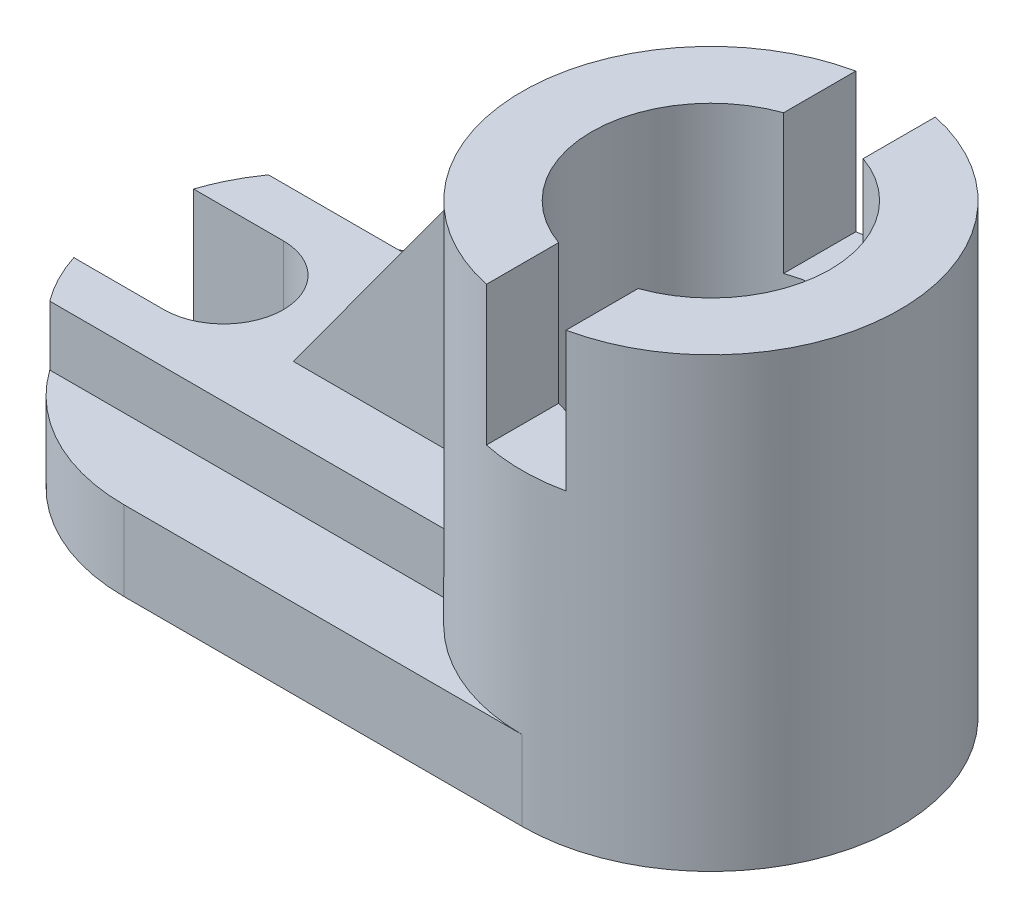
SolidWorks part; units mm, degrees
ref_plane "前视基准面" through (0, 0, 0) normal (0, 0, 1) x (1, 0, 0)
ref_plane "上视基准面" through (0, 0, 0) normal (0, 1, 0) x (1, 0, 0)
ref_plane "右视基准面" through (0, 0, 0) normal (1, 0, 0) x (0, 0, -1)
sketch "草图1" plane through (0, 0, 0) normal (0, 1, 0) x (1, 0, 0)
  circle A0 centre (0, 0) radius 19
  point P3 (-198.611, 7.7922)
sketch "草图2" plane through (0, 0, 0) normal (0, 1, 0) x (1, 0, 0)
  line L0 (-40, 19) -> (0, 19)
  line L1 (-40, -19) -> (0, -19)
  line L2 (0, 19) -> (0, -19)
  arc A0 (-40, 19) -> (-40, -19) centre (-40, 0) ccw
  circle A1 centre (0, 0) radius 19 construction
extrude "凸台-拉伸5" add sketch "草图1" along normal blind 45
extrude "凸台-拉伸7" add sketch "草图2" along normal blind 8
sketch "草图4" plane through (0, 8, 0) normal (0, 1, 0) x (1, 0, 0)
  line L0 (-10, 11) -> (-55.4919, 11)
  line L1 (-24.75, 0) -> (24.75, 0) construction
  line L2 (-10, -11) -> (-55.4919, -11)
  line L3 (-10, 11) -> (-10, -11)
  arc A1 (-40, 19) -> (-40, -19) centre (-40, 0) ccw construction
  spline S0 degree 3 poles (-55.4919, 11) (-60.0194, 4.7062) (-60.318, -4.5406) (-55.4919, -11) knots 0 0 0 0 1 1 1 1
  point P10 (0, 0)
extrude "凸台-拉伸8" add sketch "草图4" along normal blind 6
sketch "草图5" plane through (0, 14, 0) normal (0, 1, 0) x (1, 0, 0)
  line L0 (-49, 6) -> (-58.021, 6)
  line L1 (-24.75, 0) -> (24.75, 0) construction
  line L2 (-49, -6) -> (-58.021, -6)
  line L3 (-58.021, 6) -> (-65.9091, 0.8064)
  line L4 (-65.9091, 0.8064) -> (-58.021, -6)
  arc A0 (-49, -6) -> (-49, 6) centre (-49, 0) ccw
  spline S0 degree 3 poles (-55.4919, 11) (-60.0194, 4.7062) (-60.318, -4.5406) (-55.4919, -11) knots 0 0 0 0 1 1 1 1 construction
extrude "切除-拉伸2" cut sketch "草图5" against normal through all
sketch "草图7" plane through (0, 0, 0) normal (0, 0, 1) x (1, 0, 0)
  line L0 (-19, 40) -> (-38, 14)
  line L1 (-19, 45) -> (-19, 14) construction
  line L2 (-55.4919, 14) -> (-15.4919, 14) construction
  point P6 (0, 0)
  point P7 (0, 0)
rib "筋2" sketch "草图7" sketch "草图7" thickness 8 extrusion direction parallel to sketch draft on no parameters "D1"=8
sketch "草图9" plane through (0, 45, 0) normal (0, 1, 0) x (1, 0, 0)
  circle A0 centre (0, 0) radius 12
extrude "切除-拉伸3" cut sketch "草图9" against normal through all
sketch "草图10" plane through (0, 0, 0) normal (0, 0, 1) x (1, 0, 0)
  line L0 (-4, 31) -> (-4, 50)
  line L1 (0, -20.9) -> (0, 20.9) construction
  line L2 (4, 31) -> (4, 50)
  line L3 (-4, 31) -> (4, 31)
  line L4 (-4, 50) -> (4, 50)
extrude "切除-拉伸5" cut sketch "草图10" against normal through all both and the other way through all contours L4 L2 L3 L0
